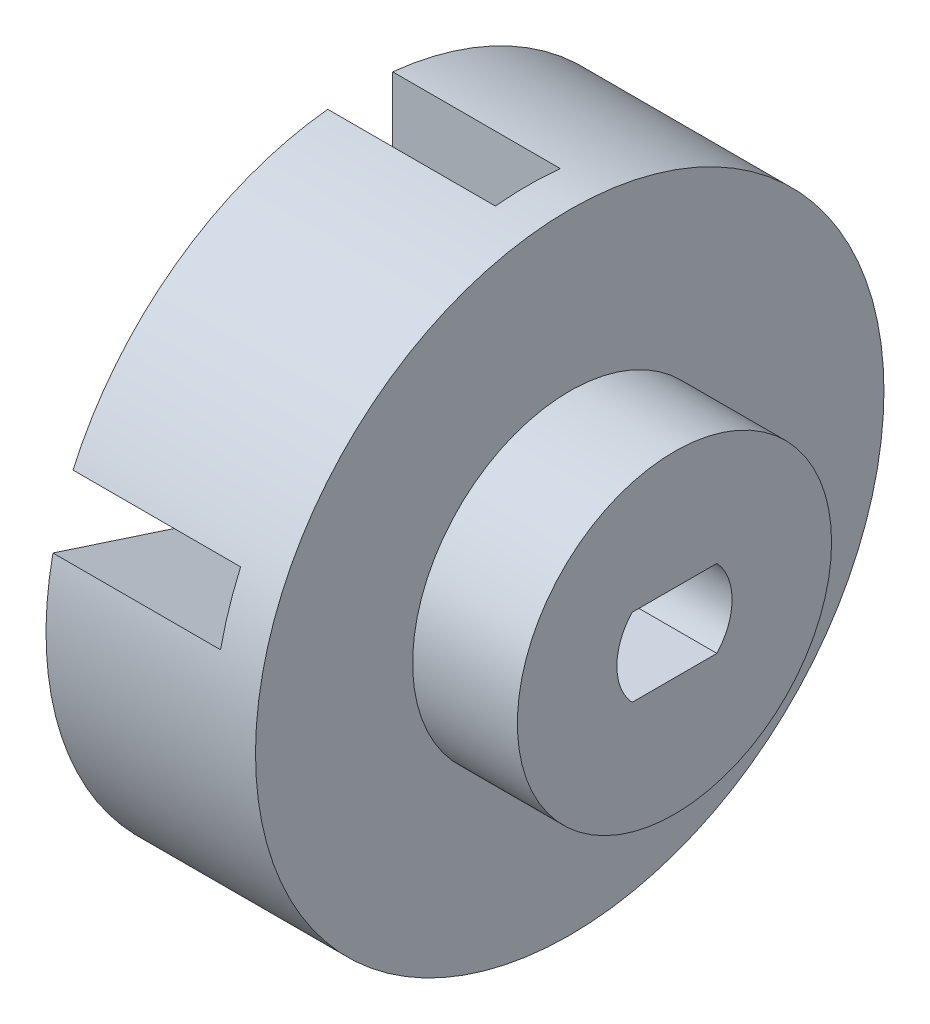
SolidWorks part; units mm, degrees
ref_plane "前视基准面" through (0, 0, 0) normal (0, 0, 1) x (1, 0, 0)
ref_plane "上视基准面" through (0, 0, 0) normal (0, 1, 0) x (1, 0, 0)
ref_plane "右视基准面" through (0, 0, 0) normal (1, 0, 0) x (0, 0, -1)
sketch "草图1" plane through (0, 0, 0) normal (1, 0, 0) x (0, 0, -1)
  circle A0 centre (0, 0) radius 15
  dimension "D1" = 30
extrude "凸台-拉伸1" add sketch "草图1" along normal blind 10
sketch "草图2" plane through (10, 0, 0) normal (1, 0, 0) x (0, 0, -1)
  circle A0 centre (0, 0) radius 7.5
  dimension "D1" = 15
extrude "凸台-拉伸2" add sketch "草图2" along normal blind 5
sketch "草图3" plane through (15, 0, 0) normal (1, 0, 0) x (0, 0, -1)
  line L0 (-2.0256, 1.86) -> (2.0256, 1.86)
  line L1 (-2.0256, -1.86) -> (2.0256, -1.86)
  arc A0 (-2.0256, 1.86) -> (-2.0256, -1.86) centre (0, 0) ccw
  arc A1 (2.0256, -1.86) -> (2.0256, 1.86) centre (0, 0) ccw
  dimension "D1" = 5.5
  dimension "D2" = 1.86
  dimension "D3" = 1.86
extrude "切除-拉伸1" cut sketch "草图3" against normal blind 5
sketch "草图4" plane through (0, 0, 0) normal (-1, 0, 0) x (0, 0, 1)
  circle A0 centre (0, 0) radius 2.7
  dimension "D1" = 5.4
extrude "切除-拉伸2" cut sketch "草图4" against normal blind 5
sketch "草图5" plane through (5, 0, 0) normal (-1, 0, 0) x (0, 0, 1)
  circle A0 centre (0, 0) radius 1.05
  dimension "D1" = 2.1
extrude "切除-拉伸3" cut sketch "草图5" against normal through all
sketch "草图6" plane through (0, 0, 0) normal (-1, 0, 0) x (0, 0, 1)
  line L0 (0, 15.9834) -> (0, -15.8667) construction
  line L1 (18.5336, 7.6517) -> (19.4916, 4.7034)
  line L2 (-1.55, 19.991) -> (1.55, 19.991)
  line L3 (-1.55, 19.991) -> (-1.55, 5)
  line L4 (-1.55, 5) -> (1.55, 5)
  line L5 (1.55, 19.991) -> (1.55, 5)
  line L6 (-1.55, 19.991) -> (1.55, 5) construction
  line L7 (-1.55, 5) -> (1.55, 19.991) construction
  line L8 (19.4916, 4.7034) -> (5.2343, 0.0709)
  line L9 (18.5336, 7.6517) -> (4.2763, 3.0192)
  line L10 (4.2763, 3.0192) -> (5.2343, 0.0709)
  line L11 (13.0044, -15.262) -> (10.4964, -17.0841)
  line L12 (10.4964, -17.0841) -> (1.6849, -4.9562)
  line L13 (13.0044, -15.262) -> (4.1929, -3.134)
  line L14 (4.1929, -3.134) -> (1.6849, -4.9562)
  line L15 (-10.4964, -17.0841) -> (-13.0044, -15.262)
  line L16 (-13.0044, -15.262) -> (-4.1929, -3.134)
  line L17 (-10.4964, -17.0841) -> (-1.6849, -4.9562)
  line L18 (-1.6849, -4.9562) -> (-4.1929, -3.134)
  line L19 (-19.4916, 4.7034) -> (-18.5336, 7.6517)
  line L20 (-18.5336, 7.6517) -> (-4.2763, 3.0192)
  line L21 (-19.4916, 4.7034) -> (-5.2343, 0.0709)
  line L22 (-5.2343, 0.0709) -> (-4.2763, 3.0192)
  point P3 (0, 12.4955)
  point P27 (0, 0)
  dimension "D1" = 3.1
  dimension "D2" = 5
  dimension "D3" = 5
extrude "切除-拉伸4" cut sketch "草图6" against normal blind 8
